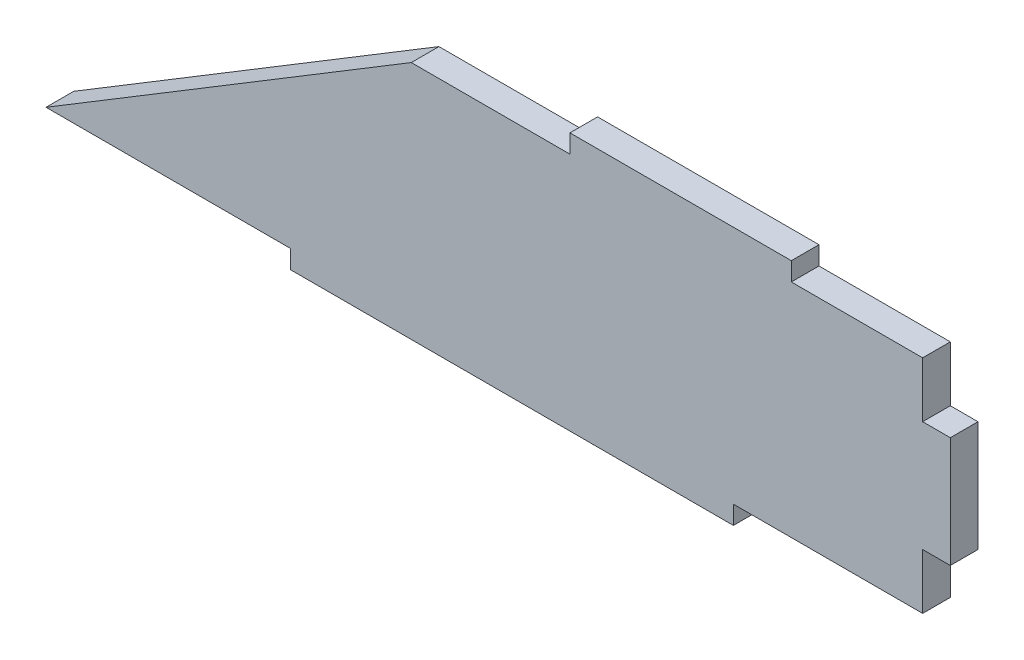
SolidWorks part; units mm, degrees
ref_plane "Front Plane" through (0, 0, 0) normal (0, 0, 1) x (1, 0, 0)
ref_plane "Top Plane" through (0, 0, 0) normal (0, 1, 0) x (1, 0, 0)
ref_plane "Right Plane" through (0, 0, 0) normal (1, 0, 0) x (0, 0, -1)
sketch "Sketch1" plane through (0, 0, 0) normal (0, 0, 1) x (1, 0, 0)
  line L0 (138.8804, 35.0708) -> (93.6684, 35.0708)
  line L1 (-162.8716, -41.1292) -> (-78.6706, -41.1292)
  line L4 (138.8804, -41.1292) -> (138.8804, -22.0792)
  line L5 (-162.8716, -41.1292) -> (138.8804, 35.0708) construction
  line L6 (-37.1416, 35.0708) -> (-162.8716, -41.1292)
  line L7 (-78.6706, -41.1292) -> (-78.6706, -47.4792)
  line L8 (-78.6706, -47.4792) -> (73.7294, -47.4792)
  line L9 (73.7294, -47.4792) -> (73.7294, -41.1292)
  line L10 (17.4684, 35.0708) -> (17.4684, 41.4208)
  line L11 (17.4684, 41.4208) -> (93.6684, 41.4208)
  line L12 (93.6684, 41.4208) -> (93.6684, 35.0708)
  line L15 (17.4684, 35.0708) -> (-37.1416, 35.0708)
  line L16 (73.7294, -41.1292) -> (138.8804, -41.1292)
  line L17 (138.8804, 16.0208) -> (148.4054, 16.0208)
  line L18 (138.8804, 16.0208) -> (138.8804, 35.0708)
  line L19 (148.4054, -22.0792) -> (138.8804, -22.0792)
  line L20 (148.4054, 16.0208) -> (148.4054, -22.0792) construction
  line L21 (148.4054, 16.0208) -> (148.4054, -22.0792)
  point P0 (0, 0)
  dimension "D2" = 301.752
  dimension "D3" = 76.2
  dimension "D4" = 6.35
  dimension "D5" = 152.4
  dimension "D6" = 6.35
  dimension "D7" = 76.2
  dimension "D8" = 45.212
  dimension "2.565" = 65.151
  dimension "D9" = 9.525
  dimension "D10" = 176.022
  dimension "D11" = 19.05
  dimension "D12" = 38.1
extrude "Boss-Extrude1" add sketch "Sketch1" along normal blind 9.525 contours L1 L7 L8 L9 L16 L4 L19 L21 L17 L18 L0 L12 L11 L10 L15 L6
